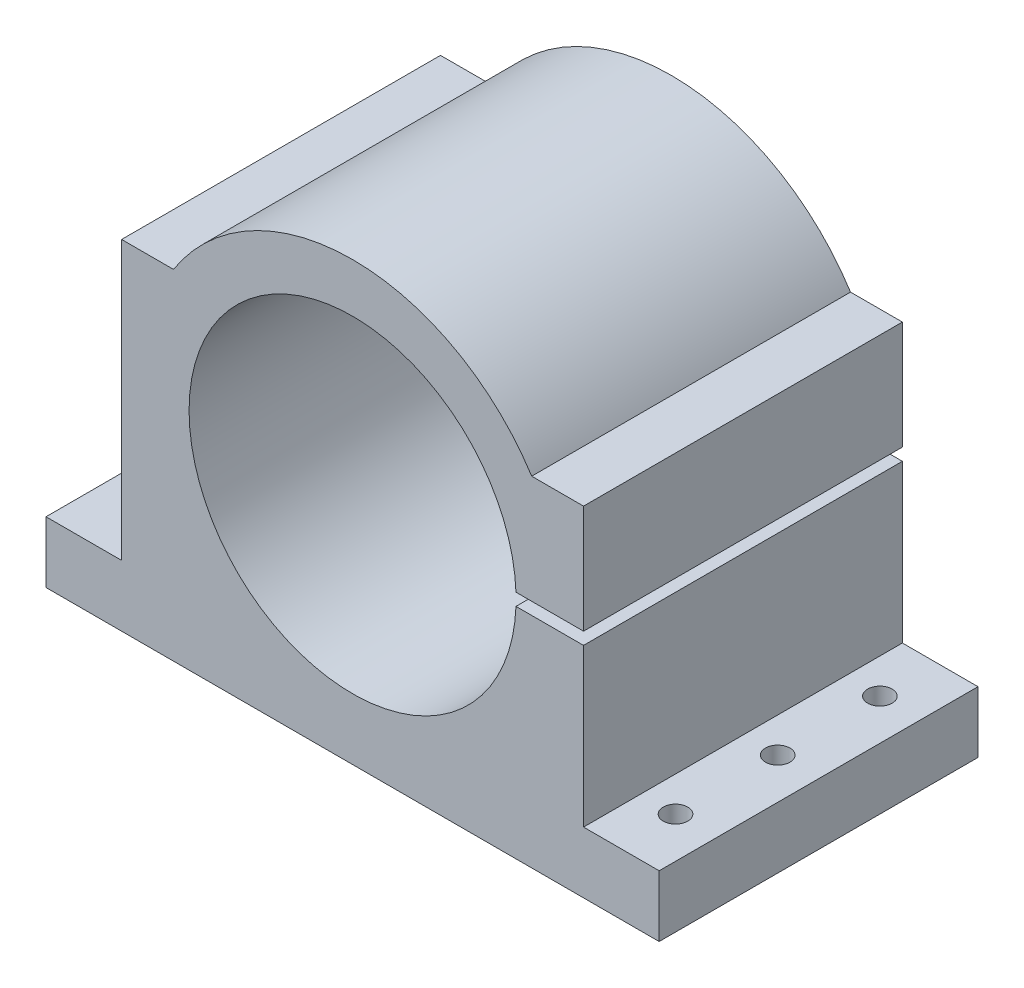
SolidWorks part; units mm, degrees
ref_plane "Plan de face" through (0, 0, 0) normal (0, 0, 1) x (1, 0, 0)
ref_plane "Plan de dessus" through (0, 0, 0) normal (0, 1, 0) x (1, 0, 0)
ref_plane "Plan de droite" through (0, 0, 0) normal (1, 0, 0) x (0, 0, -1)
sketch "Esquisse1" plane through (0, 0, 0) normal (0, 0, 1) x (1, 0, 0)
  line L0 (-75, 0) -> (75, 0)
  line L1 (75, 0) -> (75, 15)
  line L2 (75, 15) -> (56.5, 15)
  line L3 (56.5, 15) -> (56.5, 83)
  line L4 (56.5, 83) -> (43.8178, 83)
  line L5 (0, 0) -> (0, 55) construction
  line L6 (0, 55) -> (0, 107) construction
  line L7 (-56.5, 83) -> (-43.8178, 83)
  line L8 (-56.5, 15) -> (-56.5, 83)
  line L9 (-75, 15) -> (-56.5, 15)
  line L10 (-75, 0) -> (-75, 15)
  arc A0 (-43.8178, 83) -> (43.8178, 83) centre (0, 55) cw
  circle A1 centre (0, 55) radius 40
  point P9 (75, 7.5)
  dimension "D4" = 80
  dimension "D1" = 150
  dimension "D2" = 83
  dimension "D3" = 113
  dimension "D5" = 15
  dimension "D6" = 52
extrude "Boss.-Extru.1" add sketch "Esquisse1" along normal blind 78
sketch "Esquisse2" plane through (0, 0, 78) normal (0, 0, 1) x (1, 0, 0)
  line L0 (0, 55) -> (40, 55) construction
  line L1 (40, 55) -> (56.5, 55) construction
  line L2 (56.5, 15) -> (56.5, 83) construction
  line L3 (56.5, 53.5) -> (56.5, 56.5)
  line L4 (56.5, 56.5) -> (20, 56.5)
  line L5 (20, 56.5) -> (20, 53.5)
  line L6 (56.5, 53.5) -> (20, 53.5)
  circle A0 centre (0, 55) radius 40 construction
  point P12 (20, 55)
  dimension "D1" = 3
extrude "Enlèv. mat.-Extru.1" cut sketch "Esquisse2" against normal blind 78
sketch "Esquisse3" plane through (0, 15, 0) normal (0, 1, 0) x (1, 0, 0)
  line L0 (-65, -78) -> (-65, 0) construction
  line L3 (-65, -39) -> (-75, -39) construction
  line L4 (-75, -78) -> (-75, 0) construction
  line L5 (0, 0) -> (0, -78) construction
  line L6 (43.8178, 0) -> (-43.8178, 0) construction
  line L7 (-43.8178, -78) -> (43.8178, -78) construction
  line L8 (65, -39) -> (75, -39) construction
  line L9 (65, -78) -> (65, 0) construction
  circle A0 centre (-65, -39) radius 3
  circle A1 centre (-65, -14) radius 3
  circle A2 centre (-65, -64) radius 3
  circle A3 centre (65, -64) radius 3
  circle A4 centre (65, -14) radius 3
  circle A5 centre (65, -39) radius 3
  point P4 (0, 0)
  point P30 (0, 0)
  point P31 (0, 0)
  dimension "D1" = 6
  dimension "D2" = 25
  dimension "D3" = 130
extrude "Enlèv. mat.-Extru.2" cut sketch "Esquisse3" against normal up to vertex (15 mm away) up to point (75, 0, 0)
